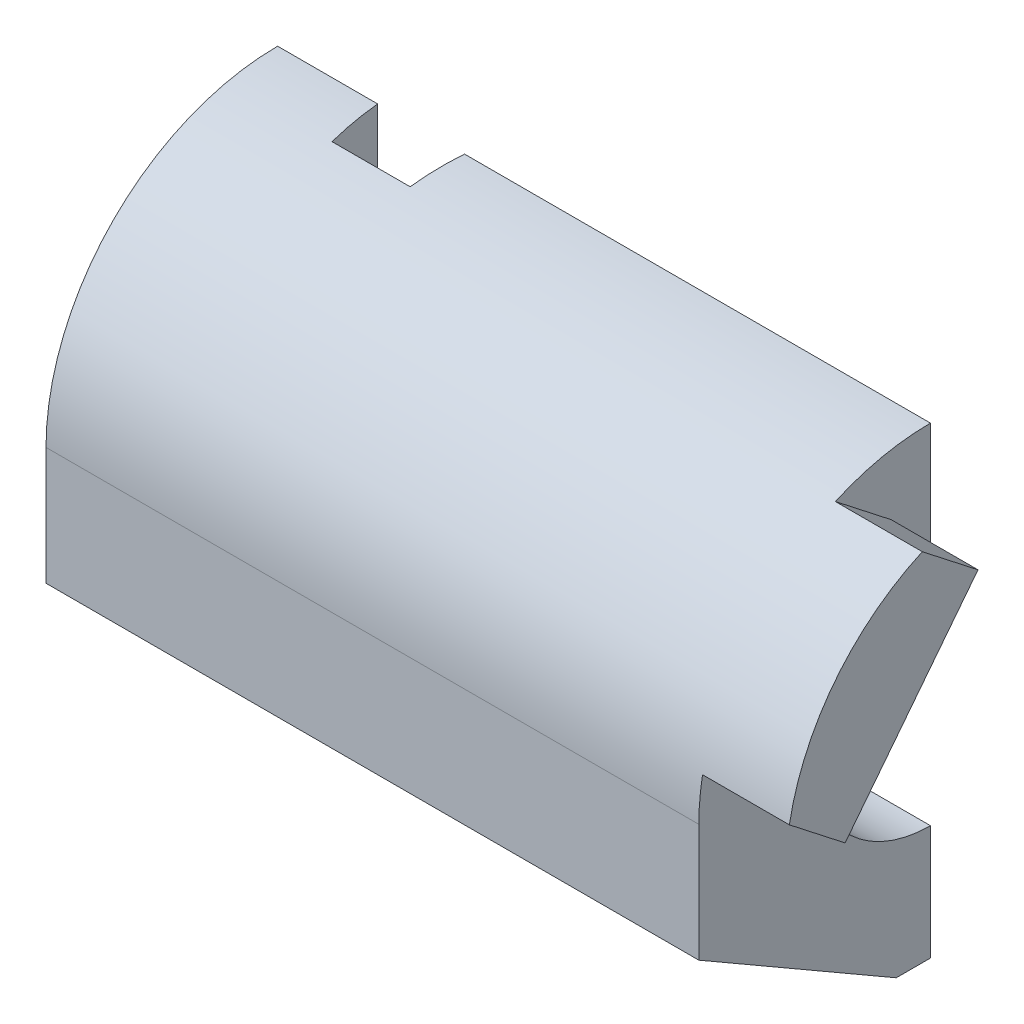
SolidWorks part; units mm, degrees
material "1060 Alloy"
ref_plane "Front Plane" through (0, 0, 0) normal (0, 0, 1) x (1, 0, 0)
ref_plane "Top Plane" through (0, 0, 0) normal (0, 1, 0) x (1, 0, 0)
ref_plane "Right Plane" through (0, 0, 0) normal (1, 0, 0) x (0, 0, -1)
sketch "Sketch1" plane through (0, 0, 0) normal (1, 0, 0) x (0, 0, -1)
  line L0 (0, 88) -> (0, -88)
  line L1 (0, -88) -> (-13, -88)
  line L2 (-13, -88) -> (-88, -44.6987)
  line L3 (-88, -44.6987) -> (-88, 0)
  arc A0 (0, 88) -> (-88, 0) centre (0, 0) ccw
  point P6 (-86, -31.5594)
  dimension "D1" = 88
  dimension "D2" = 30
  dimension "D3" = 13
  dimension "D4" = 88
extrude "Boss-Extrude1" add sketch "Sketch1" along normal mid plane 248
sketch "Sketch2" plane through (124, 0, 0) normal (1, 0, 0) x (0, 0, -1)
  circle A0 centre (0, 0) radius 44.45
  dimension "D1" = 88.9
extrude "Cut-Extrude1" cut sketch "Sketch2" against normal blind 78
sketch "Sketch3" plane through (-124, 0, 0) normal (-1, 0, 0) x (0, 0, 1)
  circle A0 centre (0, 0) radius 28.575
  dimension "D1" = 57.15
extrude "Cut-Extrude2" cut sketch "Sketch3" against normal up to surface (170 mm away) up to face at (46, 0, 22.225)
sketch "Sketch4" plane through (0, 0, 0) normal (0, 0, -1) x (-1, 0, 0)
  line L0 (124, -88) -> (124, -28.575) construction
  line L1 (124, -73) -> (11, -73)
  line L3 (124, -51) -> (11, -51)
  line L5 (-124, -88) -> (124, -88) construction
  line L7 (124, -51) -> (124, -73)
  arc A0 (11, -51) -> (11, -73) centre (11, -62) ccw
  point P0 (124, -58.2875)
  point P9 (121.5, -49.0045)
  point P10 (1.1788, -49)
  dimension "D1" = 22
  dimension "D2" = 26
  dimension "D3" = 113
extrude "Cut-Extrude3" cut sketch "Sketch4" against normal blind 13
sketch "Sketch5" plane through (0, 0, 0) normal (0, 1, 0) x (1, 0, 0)
  line L0 (124, 0) -> (-124, 0) construction
  line L1 (-53, 0) -> (-86, 0)
  line L2 (-53, 0) -> (-53, -19) construction
  line L3 (-54.6623, -19) -> (-84.3377, -19)
  line L4 (-86, 0) -> (-86, -19) construction
  line L5 (-124, 0) -> (-124, -88) construction
  line L6 (-53, 0) -> (-54.6623, -19)
  line L7 (-86, 0) -> (-84.3377, -19)
  point P10 (0, 0)
  point P11 (-54.6623, -19)
  point P12 (0, 0)
  point P13 (0, 0)
  point P14 (-53, -19)
  point P15 (-54.6623, -19)
  dimension "D1" = 19
  dimension "D2" = 33
  dimension "D3" = 38
  dimension "D5" = 5
  dimension "D6" = 19
  dimension "D4" = 5
  dimension "D7" = 19
extrude "Cut-Extrude4" cut sketch "Sketch5" along normal through all
sketch "Sketch6" plane through (124, 0, 0) normal (1, 0, 0) x (0, 0, -1)
  line L0 (-36.1165, 80.2471) -> (-14.9464, 63.7072)
  line L1 (-14.9464, 63.7072) -> (-65.4307, -0.9097)
  line L2 (-65.4307, -0.9097) -> (-86.6008, 15.6302)
  line L3 (-13, -88) -> (0, -88) construction
  line L4 (0, 0) -> (-40.1885, 31.3987) construction
  arc A0 (0, 88) -> (-88, 0) centre (0, 0) ccw construction
  arc A1 (-36.1165, 80.2471) -> (-86.6008, 15.6302) centre (0, 0) ccw
  dimension "D1" = 38
  dimension "D2" = 38
  dimension "D3" = 41
  dimension "D4" = 51
extrude "Boss-Extrude2" add sketch "Sketch6" along normal blind 33
equation "\"A\" = 248"
equation "\"B\" = 113"
equation "\"C\" = 88"
equation "\"D1@Sketch1\"=\"C\""
equation "\"D4@Sketch1\"=\"C\""
equation "\"D1@Boss-Extrude1\"=\"A\""
equation "\"D3@Sketch4\"=\"B\""
equation "\"D\"= 5"
equation "\"D1@Sketch7\"=\"D\""
equation "\"D2@Sketch7\"=\"D\""
equation "\"D5@Sketch5\"=\"D\""
equation "\"D4@Sketch5\"=\"D\""
